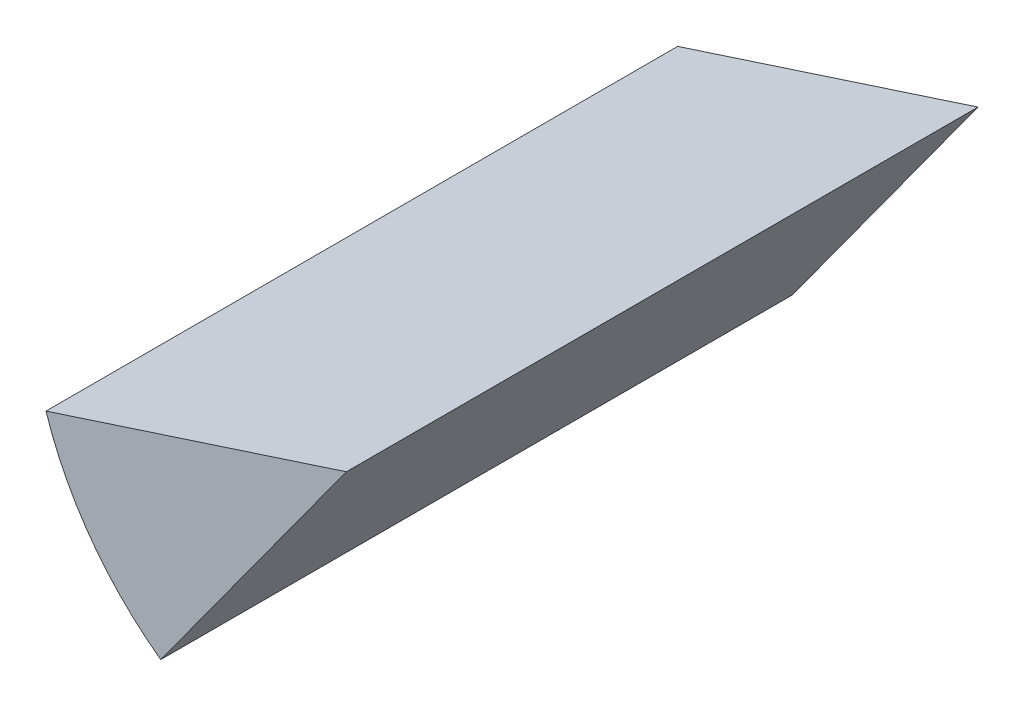
SolidWorks part; units mm, degrees
ref_plane "Alzado" through (0, 0, 0) normal (0, 0, 1) x (1, 0, 0)
ref_plane "Planta" through (0, 0, 0) normal (0, 1, 0) x (1, 0, 0)
ref_plane "Vista lateral" through (0, 0, 0) normal (1, 0, 0) x (0, 0, -1)
sketch "Croquis1" plane through (0, 0, 0) normal (0, 0, 1) x (1, 0, 0)
  line L1 (0, 0) -> (-23.7764, -7.7254)
  line L2 (0, 0) -> (-14.6946, -20.2254)
  arc A0 (-23.7764, -7.7254) -> (-14.6946, -20.2254) centre (0, 0) ccw
  dimension "D1" = 50
  dimension "D2" = 36
extrude "Saliente-Extruir1" add sketch "Croquis1" along normal blind 50
sketch "Croquis2" plane through (0, 0, 0) normal (0, 0, -1) x (-1, 0, 0)
  circle A0 centre (15.3351, -10.8052) radius 5
  dimension "D1" = 10
extrude "Cortar-Extruir1" cut sketch "Croquis2" against normal blind 10 contours A0
